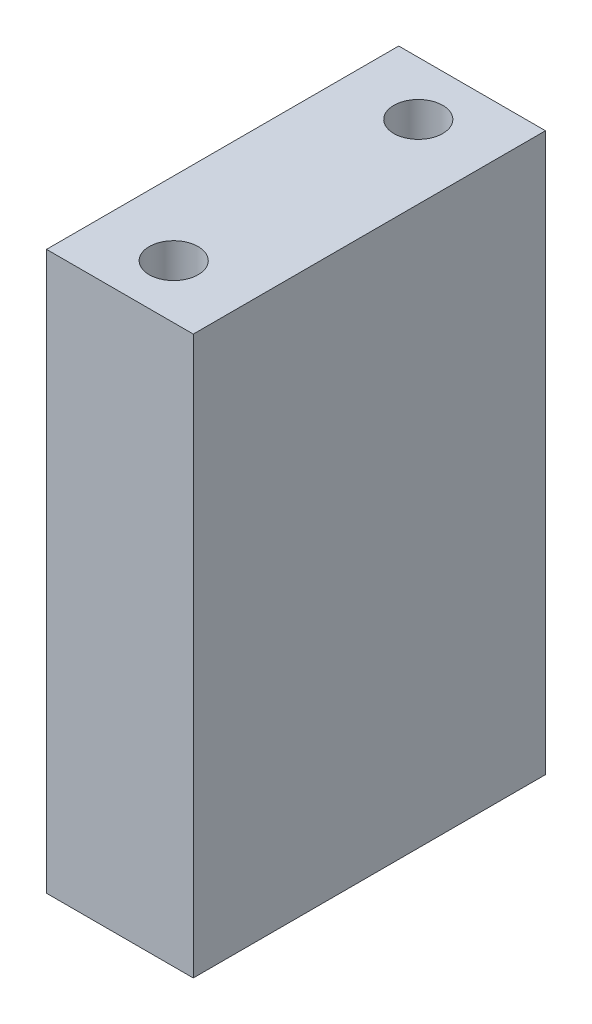
SolidWorks part; units mm, degrees
material "K110"
ref_plane "Front Plane" through (0, 0, 0) normal (0, 0, 1) x (1, 0, 0)
ref_plane "Top Plane" through (0, 0, 0) normal (0, 1, 0) x (1, 0, 0)
ref_plane "Right Plane" through (0, 0, 0) normal (1, 0, 0) x (0, 0, -1)
sketch "Sketch1" plane through (0, 0, 0) normal (0, 1, 0) x (1, 0, 0)
  line L1 (-7.5, 18) -> (7.5, 18)
  line L2 (-7.5, 18) -> (-7.5, -18)
  line L3 (-7.5, -18) -> (7.5, -18)
  line L4 (7.5, 18) -> (7.5, -18)
  line L5 (-7.5, 18) -> (7.5, -18) construction
  line L6 (-7.5, -18) -> (7.5, 18) construction
  point P0 (0, 0)
  dimension "D1" = 36
  dimension "D2" = 15
extrude "Boss-Extrude1" add sketch "Sketch1" against normal blind 57
hole_wizard "M6 Tapped Hole1" positions "Sketch5" profile "Sketch4" tap size "M6" standard "ISO"
sketch "Sketch5" plane through (0, 0, 0) normal (0, 1, 0) x (1, 0, 0)
  line L0 (7.5, 0) -> (-7.5, 0) construction
  line L1 (7.5, -18) -> (7.5, 18) construction
  line L2 (-7.5, 18) -> (-7.5, -18) construction
  point P1 (0, 12.5)
  point P3 (0, -12.5)
  point P14 (0, 0)
  point P16 (0, 0)
  dimension "D1" = 25
sketch "Sketch4" plane through (0, 0, -12.5) normal (1, 0, 0) x (0, 0, 1)
  line L0 (0, 0) -> (0, 16.5022)
  line L1 (0, 16.5022) -> (2.5, 15)
  line L2 (2.5, 15) -> (2.5, 0)
  line L5 (2.5, 0) -> (0, 0)
  line L10 (0, 16.5022) -> (-2.5, 15) construction
  line L11 (0, -6.35) -> (0, 107.95) construction
  dimension "Tap Drill Dia." = 5
  dimension "Tap Drill Depth" = 15
  dimension "Drill Angle" = 118
cosmetic thread "Hole Thread1"
cosmetic thread "Hole Thread2"
